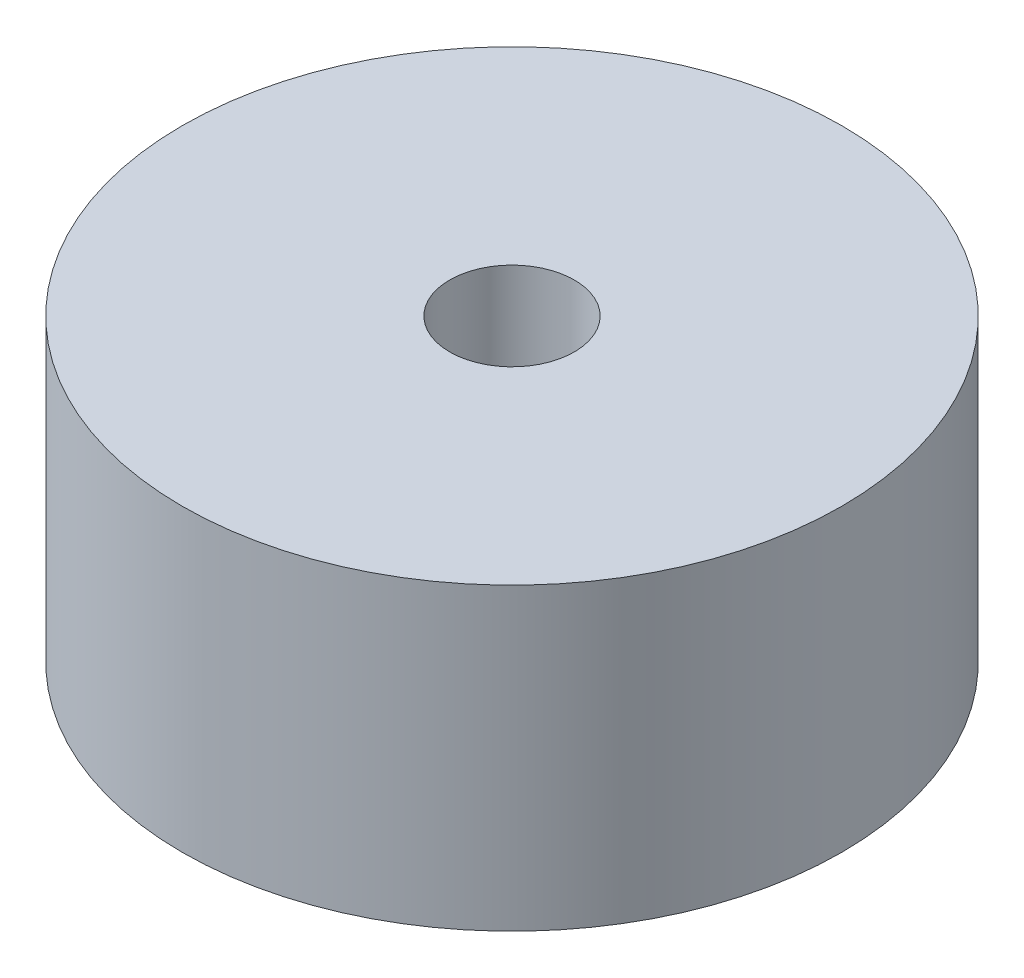
SolidWorks part; units mm, degrees
ref_plane "Front Plane" through (0, 0, 0) normal (0, 0, 1) x (1, 0, 0)
ref_plane "Top Plane" through (0, 0, 0) normal (0, 1, 0) x (1, 0, 0)
ref_plane "Right Plane" through (0, 0, 0) normal (1, 0, 0) x (0, 0, -1)
sketch "Sketch1" plane through (0, 0, 0) normal (0, 1, 0) x (1, 0, 0)
  line L0 (0, 0) -> (99.948, 0) construction
  circle A1 centre (0, 0) radius 1.04
  circle A2 centre (0, 0) radius 5.5
  dimension "D1" = 2.08
  dimension "D2" = 11
extrude "Boss-Extrude1" add sketch "Sketch1" along normal blind 5
